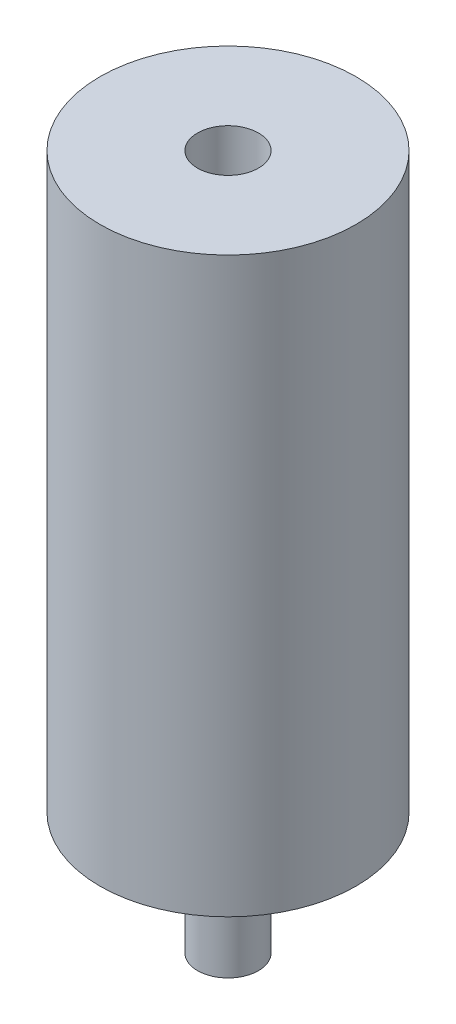
SolidWorks part; units mm, degrees
ref_plane "Front Plane" through (0, 0, 0) normal (0, 0, 1) x (1, 0, 0)
ref_plane "Top Plane" through (0, 0, 0) normal (0, 1, 0) x (1, 0, 0)
ref_plane "Right Plane" through (0, 0, 0) normal (1, 0, 0) x (0, 0, -1)
sketch "Sketch1" plane through (0, 0, 0) normal (0, 1, 0) x (1, 0, 0)
  circle A0 centre (0, 0) radius 10.5
  dimension "D1" = 21
extrude "Boss-Extrude1" add sketch "Sketch1" along normal blind 47
sketch "Sketch2" plane through (0, 47, 0) normal (0, 1, 0) x (1, 0, 0)
  circle A0 centre (0, 0) radius 2.5
  dimension "D1" = 5
extrude "Cut-Extrude1" cut sketch "Sketch2" against normal blind 10
sketch "Sketch3" plane through (0, 0, 0) normal (0, -1, 0) x (1, 0, 0)
  circle A0 centre (0, 0) radius 2.5
  dimension "D1" = 5
extrude "Boss-Extrude2" add sketch "Sketch3" along normal blind 10
